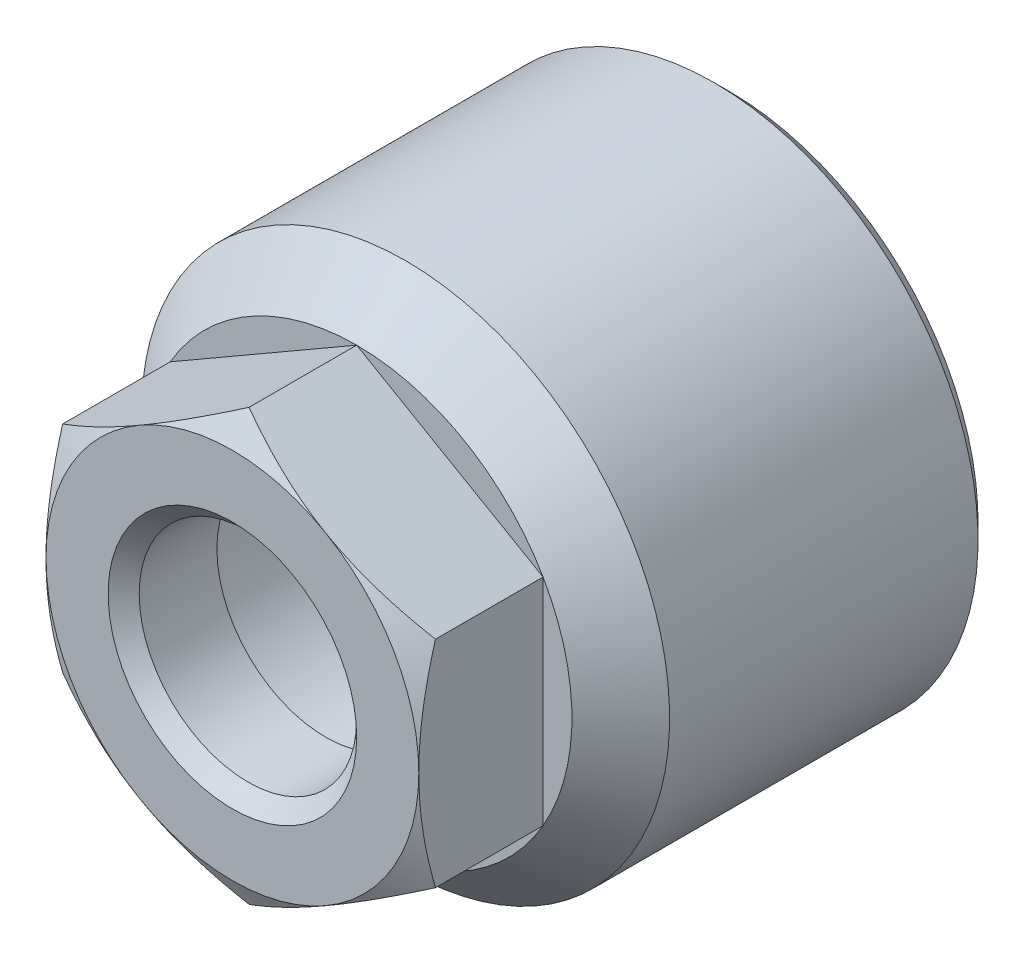
SolidWorks part; units mm, degrees
ref_plane "前视基准面" through (0, 0, 0) normal (0, 0, 1) x (1, 0, 0)
ref_plane "上视基准面" through (0, 0, 0) normal (0, 1, 0) x (1, 0, 0)
ref_plane "右视基准面" through (0, 0, 0) normal (1, 0, 0) x (0, 0, -1)
sketch "草图1" plane through (0, 0, 0) normal (0, 0, 1) x (1, 0, 0)
  line L1 (0, 13.8564) -> (-12, 6.9282)
  line L2 (-12, 6.9282) -> (-12, -6.9282)
  line L3 (-12, -6.9282) -> (0, -13.8564)
  line L4 (0, -13.8564) -> (12, -6.9282)
  line L5 (12, -6.9282) -> (12, 6.9282)
  line L6 (12, 6.9282) -> (0, 13.8564)
  circle A0 centre (0, 0) radius 12 construction
  point P1 (0, 0)
  point P10 (0, 0)
  dimension "D1" = 24
extrude "凸台-拉伸1" add sketch "草图1" against normal blind 8
sketch "草图2" plane through (0, 0, 0) normal (1, 0, 0) x (0, 0, -1)
  line L1 (8, 0) -> (8, 13.8564)
  line L2 (8, -6.9282) -> (8, 6.9282) construction
  line L3 (8, 13.8564) -> (0, 13.8564) construction
  line L4 (8, 13.8564) -> (11.1436, 17)
  line L5 (11.1436, 17) -> (32, 17)
  line L6 (32, 17) -> (32, 0)
  line L7 (4.4, 0) -> (-4.4, 0) construction
  line L8 (32, 0) -> (8, 0) construction
  line L9 (0, 13.2) -> (0, -13.2) construction
  line L10 (8, 0) -> (32, 0)
  dimension "D1" = 34
  dimension "D2" = 32
  dimension "D3" = 45
revolve "旋转1" add sketch "草图2" angle 360 about L8
sketch "草图3" plane through (0, 0, 0) normal (0, 0, 1) x (1, 0, 0)
  line L0 (12, 6.9282) -> (0, 13.8564) construction
  circle A0 centre (0, 0) radius 12
extrude "切除-拉伸1" cut sketch "草图3" against normal through all draft 60 flip side to cut
sketch "草图4" plane through (0, 0, 0) normal (1, 0, 0) x (0, 0, -1)
  line L0 (0, 0) -> (0, -7)
  line L1 (0, 18.7) -> (0, -18.7) construction
  line L2 (0, -7) -> (6, -7)
  line L3 (6, -7) -> (6, -9)
  line L4 (6, -9) -> (14, -9)
  line L5 (14, -9) -> (14, -14)
  line L6 (14, -14) -> (15, -14)
  line L7 (15, -14) -> (15, -15)
  line L8 (15, -15) -> (22, -15)
  line L9 (22, -15) -> (22, 0)
  line L10 (17.6, 0) -> (-17.6, 0) construction
  line L11 (22, 0) -> (0, 0) construction
  line L12 (0, 0) -> (22, 0)
  dimension "D1" = 6
  dimension "D2" = 8
  dimension "D3" = 1
  dimension "D4" = 7
  dimension "D5" = 14
  dimension "D6" = 18
  dimension "D7" = 30
  dimension "D8" = 28
revolve "切除-旋转1" cut sketch "草图4" angle 360 about L11
hole_wizard "M30 螺纹孔1" positions "草图5" profile "草图6" tap size "M30" standard "GB"
sketch "草图5" plane through (0, 0, -32) normal (0, 0, -1) x (-1, 0, 0)
  point P0 (0, 0)
sketch "草图6" plane through (0, 0, -32) normal (1, 0, 0) x (0, 1, 0)
  line L0 (0, 0) -> (0, 10)
  line L1 (0, 10) -> (13.25, 10)
  line L2 (13.25, 10) -> (13.25, 0)
  line L5 (13.25, 0) -> (0, 0)
  line L11 (0, -6.35) -> (0, 107.95) construction
  dimension "通孔螺纹孔钻头直径" = 26.5
  dimension "通孔螺纹孔钻头深度" = 10
cosmetic thread "孔螺纹线1" parameters "D2"=30
chamfer "倒角1" distance 1 angle 45 1 edges at (0, 17, -32)
chamfer "倒角2" distance 1 angle 45 2 edges at (-7, 0, 0) (-9, 0, -14)
